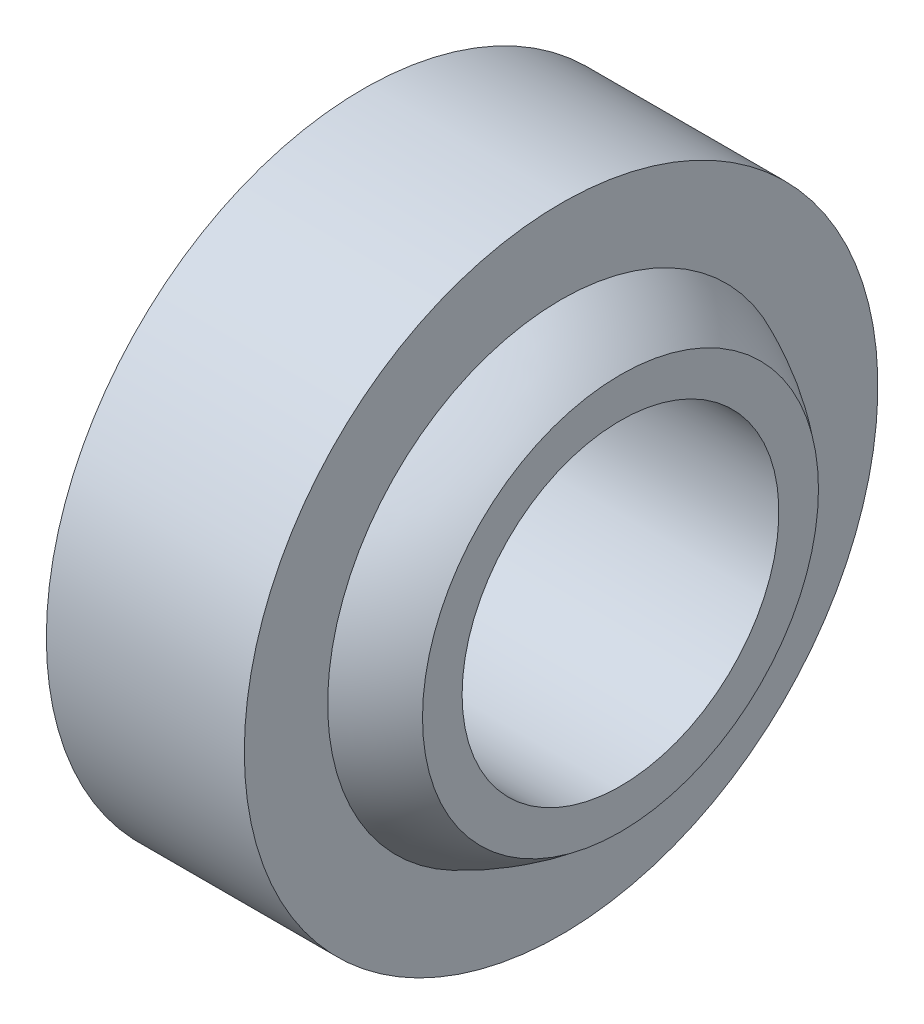
SolidWorks part; units mm, degrees
ref_plane "前视基准面" through (0, 0, 0) normal (0, 0, 1) x (1, 0, 0)
ref_plane "上视基准面" through (0, 0, 0) normal (0, 1, 0) x (1, 0, 0)
ref_plane "右视基准面" through (0, 0, 0) normal (1, 0, 0) x (0, 0, -1)
other "Configuration Table"
sketch "草图1" plane through (0, 0, 0) normal (0, 0, 1) x (1, 0, 0)
  line L0 (0, 0) -> (13.3999, 0) construction
  line L2 (4.4432, 5.8949) -> (4.4432, 8)
  line L3 (4.4432, 8) -> (-0.5568, 8)
  line L4 (-0.5568, 8) -> (-0.5568, 5.8949)
  line L5 (-2.0568, 5) -> (-2.0568, 4)
  line L6 (-2.0568, 4) -> (5.9432, 4)
  line L7 (1.9432, 5.6272) -> (1.9432, 8) construction
  line L8 (5.9432, 5) -> (5.9432, 4)
  arc A1 (4.4432, 5.8949) -> (5.9432, 5) centre (1.9432, 0) cw
  arc A2 (-0.5568, 5.8949) -> (-2.0568, 5) centre (1.9432, 0) ccw
  dimension "D1" = 8
  dimension "D2" = 8
  dimension "D3" = 4
  dimension "D4" = 5
  dimension "D5" = 5
revolve "旋转1" add sketch "草图1" angle 360 about L0
